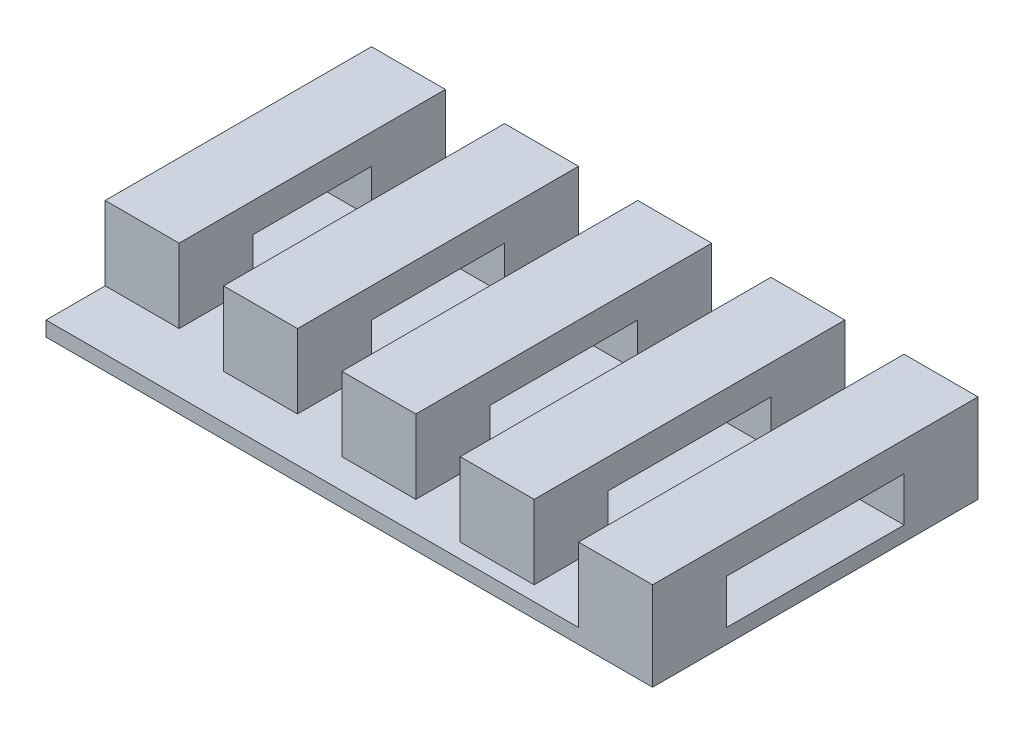
SolidWorks part; units mm, degrees
ref_plane "Front Plane" through (0, 0, 0) normal (0, 0, 1) x (1, 0, 0)
ref_plane "Top Plane" through (0, 0, 0) normal (0, 1, 0) x (1, 0, 0)
ref_plane "Right Plane" through (0, 0, 0) normal (1, 0, 0) x (0, 0, -1)
sketch "Sketch1" plane through (0, 0, 0) normal (0, 1, 0) x (1, 0, 0)
  line L1 (0, 0) -> (41, 0)
  line L2 (0, 0) -> (0, 22)
  line L3 (0, 22) -> (41, 22)
  line L4 (41, 0) -> (41, 22)
  dimension "D1" = 22
  dimension "D2" = 41
extrude "Base" add sketch "Sketch1" along normal blind 1 contours L2 L3 L4 L1
sketch "Sketch2" plane through (0, 1, 0) normal (0, 1, 0) x (1, 0, 0)
  line L0 (0, 0) -> (0, 22) construction
  line L1 (0, 22) -> (5, 22)
  line L2 (0, 22) -> (0, 17)
  line L3 (0, 17) -> (5, 17)
  line L4 (5, 22) -> (5, 17)
  line L5 (0, 9) -> (5, 9)
  line L6 (0, 9) -> (0, 4)
  line L7 (0, 4) -> (5, 4)
  line L8 (5, 9) -> (5, 4)
  line L9 (0, 22) -> (41, 22) construction
  line L10 (41, 0) -> (36, 0)
  line L11 (41, 0) -> (41, 5)
  line L12 (41, 5) -> (36, 5)
  line L13 (36, 0) -> (36, 5)
  line L14 (41, 22) -> (36, 22)
  line L15 (41, 22) -> (41, 17)
  line L16 (41, 17) -> (36, 17)
  line L17 (36, 22) -> (36, 17)
  line L18 (9, 22) -> (14, 22)
  line L19 (9, 22) -> (9, 17)
  line L20 (9, 17) -> (14, 17)
  line L21 (14, 22) -> (14, 17)
  line L23 (9, 8) -> (14, 8)
  line L24 (9, 8) -> (9, 3)
  line L25 (9, 3) -> (14, 3)
  line L26 (14, 8) -> (14, 3)
  line L27 (18, 17) -> (23, 17)
  line L28 (18, 17) -> (18, 22)
  line L29 (18, 22) -> (23, 22)
  line L30 (23, 17) -> (23, 22)
  line L31 (27, 22) -> (32, 22)
  line L32 (27, 22) -> (27, 17)
  line L33 (27, 17) -> (32, 17)
  line L34 (32, 22) -> (32, 17)
  line L35 (18, 7) -> (23, 7)
  line L36 (18, 7) -> (18, 2)
  line L37 (18, 2) -> (23, 2)
  line L38 (23, 7) -> (23, 2)
  line L39 (27, 6) -> (32, 6)
  line L40 (27, 6) -> (27, 1)
  line L41 (27, 1) -> (32, 1)
  line L42 (32, 6) -> (32, 1)
  dimension "D1" = 5
  dimension "D2" = 5
  dimension "D3" = 8
  dimension "D4" = 5
  dimension "D5" = 5
  dimension "D6" = 5
  dimension "D7" = 12
  dimension "D8" = 5
  dimension "D9" = 9
  dimension "D10" = 5
  dimension "D11" = 5
  dimension "D12" = 4
  dimension "D14" = 4
  dimension "D15" = 5
  dimension "D16" = 4
  dimension "D17" = 5
  dimension "D18" = 4
  dimension "D19" = 10
  dimension "D20" = 11
  dimension "D21" = 5
  dimension "D22" = 5
  dimension "D23" = 5
  dimension "D24" = 5
extrude "Legs_Extrusion" add sketch "Sketch2" along normal blind 5
sketch "Sketch3" plane through (0, 0, -17) normal (0, 0, 1) x (1, 0, 0)
  line L0 (5, 6) -> (5, 1) construction
  line L1 (0, 6) -> (5, 6)
  line L2 (0, 6) -> (0, 4)
  line L3 (0, 4) -> (5, 4)
  line L4 (5, 6) -> (5, 4)
  dimension "D1" = 2
sketch "Sketch4" plane through (0, 0, -17) normal (0, 0, 1) x (1, 0, 0)
  line L0 (14, 6) -> (14, 1) construction
  line L1 (9, 6) -> (14, 6)
  line L2 (9, 6) -> (9, 4)
  line L3 (9, 4) -> (14, 4)
  line L4 (14, 6) -> (14, 4)
  dimension "D1" = 2
sketch "Sketch6" plane through (0, 0, -17) normal (0, 0, 1) x (1, 0, 0)
  line L0 (23, 6) -> (23, 1) construction
  line L1 (18, 6) -> (23, 6)
  line L2 (18, 6) -> (18, 4)
  line L3 (18, 4) -> (23, 4)
  line L4 (23, 6) -> (23, 4)
  dimension "D1" = 2
sketch "Sketch7" plane through (0, 0, -17) normal (0, 0, 1) x (1, 0, 0)
  line L0 (32, 6) -> (32, 1) construction
  line L1 (27, 6) -> (32, 6)
  line L2 (27, 6) -> (27, 4)
  line L3 (27, 4) -> (32, 4)
  line L4 (32, 6) -> (32, 4)
  dimension "D1" = 2
sketch "Sketch8" plane through (0, 0, -17) normal (0, 0, 1) x (1, 0, 0)
  line L0 (41, 6) -> (41, 1) construction
  line L1 (36, 6) -> (41, 6)
  line L2 (36, 6) -> (36, 4)
  line L3 (36, 4) -> (41, 4)
  line L4 (41, 6) -> (41, 4)
  dimension "D1" = 2
extrude "bridge1" add sketch "Sketch3" along normal blind 8
extrude "bridge2" add sketch "Sketch4" along normal blind 9
extrude "bridge3" add sketch "Sketch6" along normal blind 10
extrude "bridge4" add sketch "Sketch7" along normal blind 11
extrude "bridge5" add sketch "Sketch8" along normal blind 12
